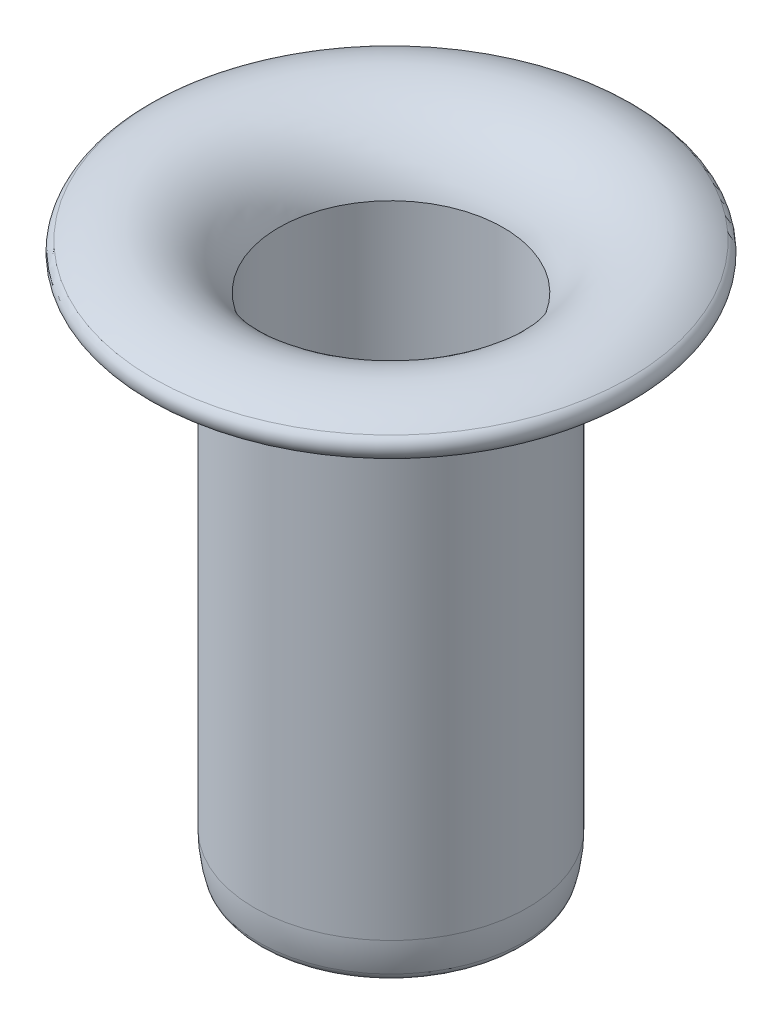
SolidWorks part; units mm, degrees
ref_plane "Front Plane" through (0, 0, 0) normal (0, 0, 1) x (1, 0, 0)
ref_plane "Top Plane" through (0, 0, 0) normal (0, 1, 0) x (1, 0, 0)
ref_plane "Right Plane" through (0, 0, 0) normal (1, 0, 0) x (0, 0, -1)
sketch "Sketch1" plane through (0, 0, 0) normal (1, 0, 0) x (0, 0, -1)
  line L0 (1.29, -0.5) -> (1.29, -5.3)
  line L1 (1.165, -0.4792) -> (1.165, -5.3)
  line L2 (1.415, -0.5227) -> (1.415, -5.3)
  line L3 (0, 0) -> (0, -5.0052) construction
  arc A0 (2.405, -0.118) -> (1.29, -0.5) centre (2, -0.7541) ccw
  arc A1 (1.25, -5.6) -> (1.29, -5.3) centre (0.145, -5.3) ccw
  arc A2 (1.1294, -5.5672) -> (1.165, -5.3) centre (0.145, -5.3) ccw
  arc A3 (2.4721, -0.0125) -> (1.165, -0.4792) centre (2, -0.7541) ccw
  arc A4 (1.3706, -5.6328) -> (1.415, -5.3) centre (0.145, -5.3) ccw
  arc A5 (2.3379, -0.2234) -> (1.415, -0.5227) centre (2, -0.7541) ccw
  arc A6 (1.1294, -5.5672) -> (1.3706, -5.6328) centre (1.25, -5.6) ccw
  arc A7 (2.4721, -0.0125) -> (2.3379, -0.2234) centre (2.405, -0.118) cw
  point P5 (2.405, -0.118)
  point P10 (2, 0)
  dimension "D1" = 2.405
  dimension "D2" = 1.29
  dimension "D3" = 1.25
  dimension "D4" = 0.3
  dimension "D5" = 5.6
  dimension "D6" = 0.5
  dimension "D7" = 2
  dimension "D8" = 0.125
  dimension "D9" = 0.125
revolve "Revolve1" add sketch "Sketch1" angle 360 about L3
